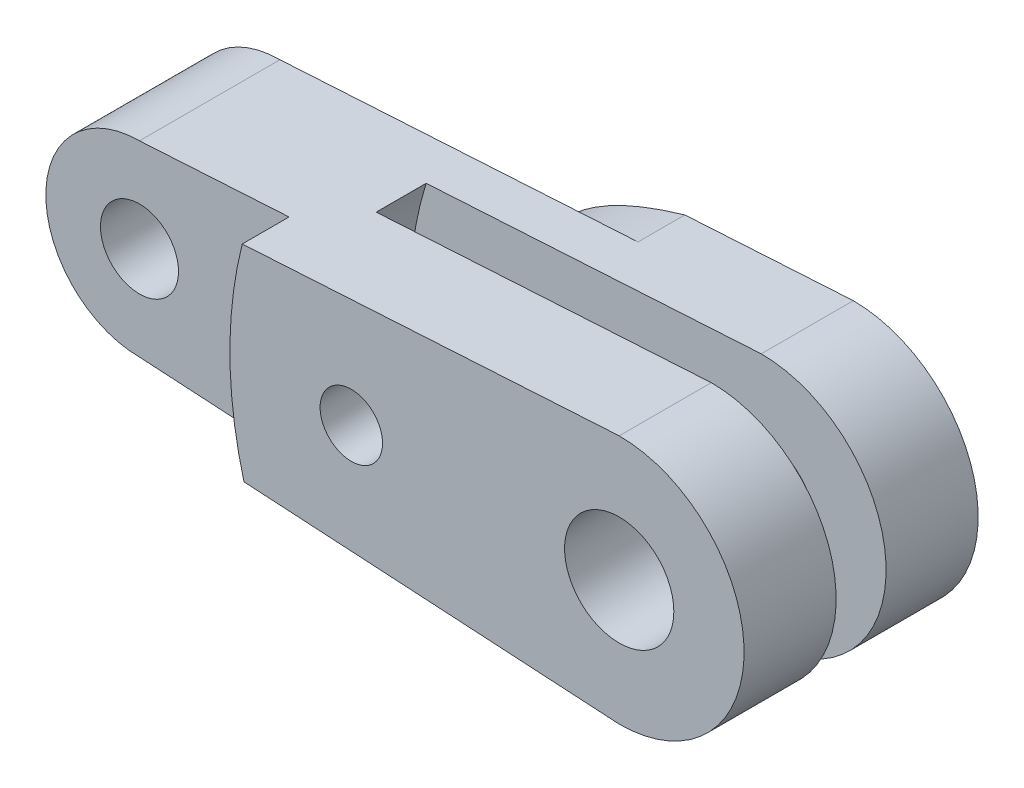
SolidWorks part; units mm, degrees
ref_plane "Спереди" through (0, 0, 0) normal (0, 0, 1) x (1, 0, 0)
ref_plane "Сверху" through (0, 0, 0) normal (0, 1, 0) x (1, 0, 0)
ref_plane "Справа" through (0, 0, 0) normal (1, 0, 0) x (0, 0, -1)
sketch "Эскиз1" plane through (0, 0, 0) normal (0, 0, 1) x (1, 0, 0)
  line L1 (-33.7379, 6) -> (0, 8)
  line L2 (-33.7379, -6) -> (0, -8)
  circle A0 centre (0, 0) radius 3.5
  arc A1 (0, -8) -> (0, 8) centre (0, 0) ccw
  arc A2 (-33.7379, 6) -> (-33.7379, -6) centre (-33.7379, 0) ccw
extrude "Вытянуть1" add sketch "Эскиз1" along normal blind 15
sketch "Эскиз2" plane through (0, 0, 9.1) normal (0, 0, 1) x (1, 0, 0)
  line L0 (0, 8) -> (-33.7379, 6) construction
  line L1 (-33.7379, -6) -> (0, -8) construction
  line L2 (-21.4708, 6.7272) -> (-0.6494, 7.9736)
  line L3 (-21.4708, -6.7272) -> (-0.6494, -7.9736)
  line L4 (-0.6494, 7.9736) -> (-0.6494, 12.4648)
  line L5 (-0.6494, 12.4648) -> (11.5317, 12.4648)
  line L6 (11.5317, 12.4648) -> (11.5317, -11.5836)
  line L7 (11.5317, -11.5836) -> (-0.6494, -11.5836)
  line L8 (-0.6494, -11.5836) -> (-0.6494, -7.9736)
  arc A1 (-21.4708, 6.7272) -> (-21.4708, -6.7272) centre (0, 0) ccw
  circle A2 centre (0, 0) radius 22.5 construction
extrude "Вырез-Вытянуть1" cut sketch "Эскиз2" against normal blind 3.2
sketch "Эскиз3" plane through (0, 0, 15) normal (0, 0, 1) x (1, 0, 0)
  line L1 (-58.5852, 9.3207) -> (-23.29, 9.3207)
  line L2 (-58.5852, 9.3207) -> (-58.5852, -8.9095)
  line L3 (-58.5852, -8.9095) -> (-23.29, -8.9095)
  arc A0 (-23.29, 9.3207) -> (-23.29, -8.9095) centre (0.9712, 0.2056) ccw
extrude "Вырез-Вытянуть2" cut sketch "Эскиз3" against normal blind 3
sketch "Эскиз4" plane through (0, 0, 0) normal (0, 0, -1) x (-1, 0, 0)
  line L0 (7.5019, 8.1689) -> (7.5019, 9.2255)
  line L1 (56.4236, 9.2255) -> (7.5019, 9.2255)
  line L2 (56.4236, 9.2255) -> (56.4236, -10.7458)
  line L3 (56.4236, -10.7458) -> (16.6085, -10.7458)
  line L4 (16.6085, -7.8716) -> (16.6085, -10.7458)
  spline S0 degree 2 poles (7.5019, 8.1689) (26.5456, 4.1985) (16.6085, -7.8716) knots 0 0 0 1 1 1
extrude "Вырез-Вытянуть3" cut sketch "Эскиз4" against normal blind 3
sketch "Эскиз5" plane through (0, 0, 12) normal (0, 0, 1) x (1, 0, 0)
  circle A0 centre (-33.7379, 0) radius 2.5
extrude "Вырез-Вытянуть4" cut sketch "Эскиз5" against normal blind 15
sketch "Эскиз6" plane through (0, 0, 15) normal (0, 0, 1) x (1, 0, 0)
  circle A0 centre (-17.1656, 0) radius 2
extrude "Вырез-Вытянуть5" cut sketch "Эскиз6" against normal blind 15
